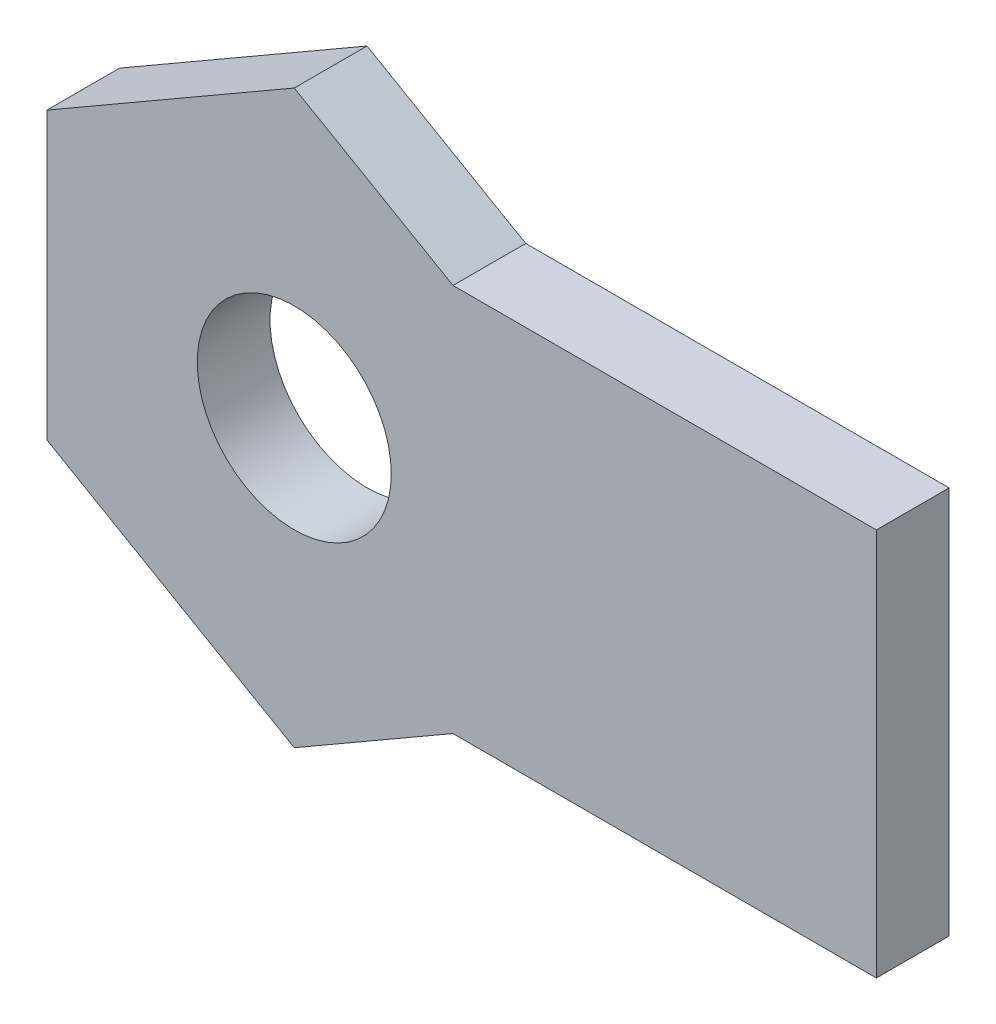
SolidWorks part; units mm, degrees
ref_plane "Front Plane" through (0, 0, 0) normal (0, 0, 1) x (1, 0, 0)
ref_plane "Top Plane" through (0, 0, 0) normal (0, 1, 0) x (1, 0, 0)
ref_plane "Right Plane" through (0, 0, 0) normal (1, 0, 0) x (0, 0, -1)
sketch "Sketch1" plane through (0, 0, 0) normal (0, 0, 1) x (1, 0, 0)
  line L0 (0, 55.2178) -> (0, -55.2178) construction
  line L3 (120, 50) -> (120, -50) construction
  line L5 (0, 50) -> (0, -50) construction
  line L7 (120, 0) -> (0, 0) construction
  line L9 (0, 0) -> (-33.9834, 58.8611) construction
  line L10 (32.718, 40) -> (120, 40)
  line L12 (-0.8858, -22.4657) -> (0, -21.9542)
  line L32 (0, -20) -> (0, -21.9542)
  line L33 (32.718, -40) -> (120, -40)
  line L34 (120, 40) -> (120, -40)
  line L35 (-58.8897, 0) -> (211.0119, 0) construction
  line L38 (0, -58.8897) -> (32.718, -40)
  line L40 (32.718, 40) -> (0, 58.8897)
  line L41 (0, 58.8897) -> (-51, 29.4449)
  line L42 (-51, 29.4449) -> (-51, -29.4449)
  line L43 (-51, -29.4449) -> (0, -58.8897)
  line L44 (51, 0) -> (51, 29.4449) [skipped]
  circle A1 centre (0, 0) radius 20
  arc A4 (25.5, 44.1673) -> (25.5, -44.1673) centre (0, 0) ccw construction
  point P10 (0, 0)
  point P12 (32.718, 40)
  point P23 (32.718, -40)
  dimension "D1" = 102
  dimension "D2" = 40
  dimension "D3" = 80
  dimension "D4" = 120
extrude "Boss-Extrude1" add sketch "Sketch1" along normal blind 15
fillet "Fillet1" [suppressed] radius 2
sketch "Sketch2" [suppressed] plane through (-33.9834, -58.8611, 0) normal (-0.5, -0.866, 0) x (0.866, -0.5, 0)
  line L0 (21.6648, 7.5) -> (-21.6648, 7.5) construction
  line L1 (21.6648, 0) -> (21.6648, 15) construction
  line L2 (-21.6648, 15) -> (-21.6648, 0) construction
  line L3 (0, 15) -> (0, 0) construction
  line L4 (-7.5, 3.1777) -> (7.5, 3.1777) construction
  line L5 (-7.5, 3.1777) -> (-7.5, 11.8223) construction
  line L6 (-7.5, 11.8223) -> (7.5, 11.8223) construction
  line L7 (7.5, 3.1777) -> (7.5, 11.8223) construction
  line L8 (-7.5, 3.1777) -> (7.5, 11.8223) construction
  line L9 (-7.5, 11.8223) -> (7.5, 3.1777) construction
  line L10 (-21.6648, 15) -> (21.6648, 15) construction
  circle A0 centre (-7.5, 7.5) radius 3.4
  circle A1 centre (7.5, 7.5) radius 3.4
  point P6 (0, 7.5)
  point P7 (0, 7.5)
  dimension "D2" = 6.8
  dimension "D1" = 15
extrude "Cut-Extrude1" [suppressed] cut sketch "Sketch2" against normal mid plane 84
mirror "Mirror1" [suppressed] about plane through (0, 0, 0) normal (0, 1, 0)
sketch "Sketch3" [suppressed] plane through (0, 0, 0) normal (0, 0, -1) x (-1, 0, 0)
  line L0 (33.9834, 58.8611) -> (0, 0) construction
  line L1 (52.7457, 48.0287) -> (15.2212, 69.6934) construction
  line L2 (0, 0) -> (-18.5959, -32.209) construction
  line L3 (94.5718, 23.8804) -> (33.7155, -81.5258) construction
  line L4 (94.5718, 23.8804) -> (0.4492, 78.2221) construction
  line L5 (33.7155, -81.5258) -> (-60.4071, -27.1841) construction
  line L6 (0.4492, 78.2221) -> (-60.4071, -27.1841) construction
  line L7 (-20.8888, -50) -> (-20.8888, 50) construction
  line L8 (-120, -50) -> (-23.4307, -50) construction
  line L9 (-120, 50) -> (-23.4307, 50) construction
  arc A0 (12.4892, -68.9614) -> (15.2212, -69.6934) centre (14.2212, -67.9614) ccw construction
  arc A1 (52.7457, -48.0287) -> (53.4777, -45.2966) centre (51.7457, -46.2966) ccw construction
